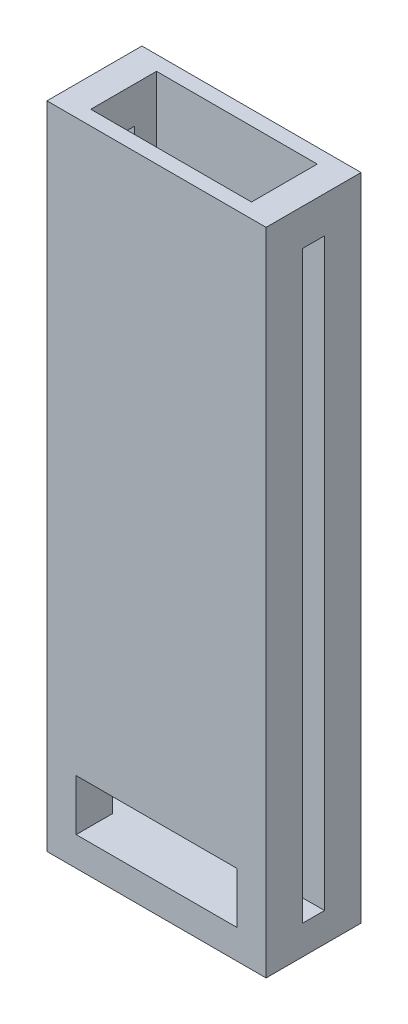
SolidWorks part; units mm, degrees
ref_plane "Front Plane" through (0, 0, 0) normal (0, 0, 1) x (1, 0, 0)
ref_plane "Top Plane" through (0, 0, 0) normal (0, 1, 0) x (1, 0, 0)
ref_plane "Right Plane" through (0, 0, 0) normal (1, 0, 0) x (0, 0, -1)
sketch "Sketch1" plane through (0, 0, 0) normal (0, 1, 0) x (1, 0, 0)
  line L1 (0, 0) -> (30, 0)
  line L2 (0, 0) -> (0, -13)
  line L3 (0, -13) -> (30, -13)
  line L4 (30, 0) -> (30, -13)
  dimension "D1" = 30
  dimension "D2" = 13
extrude "Boss-Extrude1" add sketch "Sketch1" along normal blind 85
sketch "Sketch2" plane through (0, 85, 0) normal (0, 1, 0) x (1, 0, 0)
  line L0 (0, -6.5) -> (30, -6.5) construction
  line L1 (0, 0) -> (0, -13) construction
  line L2 (30, -13) -> (30, 0) construction
  line L4 (4, -11) -> (26, -11)
  line L5 (4, -11) -> (4, -2)
  line L6 (4, -2) -> (26, -2)
  line L7 (26, -11) -> (26, -2)
  line L8 (4, -11) -> (26, -2) construction
  line L9 (4, -2) -> (26, -11) construction
  point P6 (15, -6.5)
  dimension "D1" = 22
  dimension "D2" = 9
extrude "Cut-Extrude2" cut sketch "Sketch2" against normal blind 85
sketch "Sketch5" plane through (0, 0, 0) normal (0, 1, 0) x (1, 0, 0)
  line L1 (0, 0) -> (30, 0)
  line L2 (0, 0) -> (0, -13)
  line L3 (0, -13) -> (30, -13)
  line L4 (30, 0) -> (30, -13)
extrude "Boss-Extrude3" add sketch "Sketch5" against normal blind 4
sketch "Sketch7" plane through (0, 85, 0) normal (0, 1, 0) x (1, 0, 0)
  line L0 (4, -13) -> (4, 0) construction
  line L1 (0, -13) -> (30, -13) construction
  line L2 (30, 0) -> (0, 0) construction
  line L3 (26, -13) -> (26, 0) construction
sketch "Sketch10" plane through (0, 85, 0) normal (0, 1, 0) x (1, 0, 0)
  line L0 (4, -13) -> (0, -13) construction
sketch "Sketch12" plane through (0, 0, 13) normal (0, 0, 1) x (1, 0, 0)
  line L0 (0, -4) -> (0, 0) construction
  line L1 (0, 85) -> (0, -4) construction
  line L2 (0, -4) -> (4, -4) construction
  line L3 (0, -4) -> (30, -4) construction
  line L4 (4, -4) -> (4, 0) construction
  line L5 (4, 0) -> (4, 7) construction
  line L7 (4, 0) -> (26, 0)
  line L8 (4, 0) -> (4, 7)
  line L9 (4, 7) -> (26, 7)
  line L10 (26, 0) -> (26, 7)
  dimension "D1" = 22
extrude "Cut-Extrude4" cut sketch "Sketch12" against normal blind 13 contours L9 L10 L7 L8
sketch "Sketch13" plane through (0, 0, 0) normal (-1, 0, 0) x (0, 0, 1)
  line L0 (0, -4) -> (13, -4) construction
  line L1 (5, -4) -> (8, -4) construction
  line L2 (6.5, -4) -> (6.5, 0) construction
  line L3 (6.5, 0) -> (5, 0) construction
  line L5 (5, 0) -> (8, 0)
  line L6 (5, 0) -> (5, 80)
  line L7 (5, 80) -> (8, 80)
  line L8 (8, 0) -> (8, 80)
  point P7 (6.5, -4)
  dimension "D1" = 3
  dimension "D2" = 80
extrude "Cut-Extrude5" cut sketch "Sketch13" against normal through all
